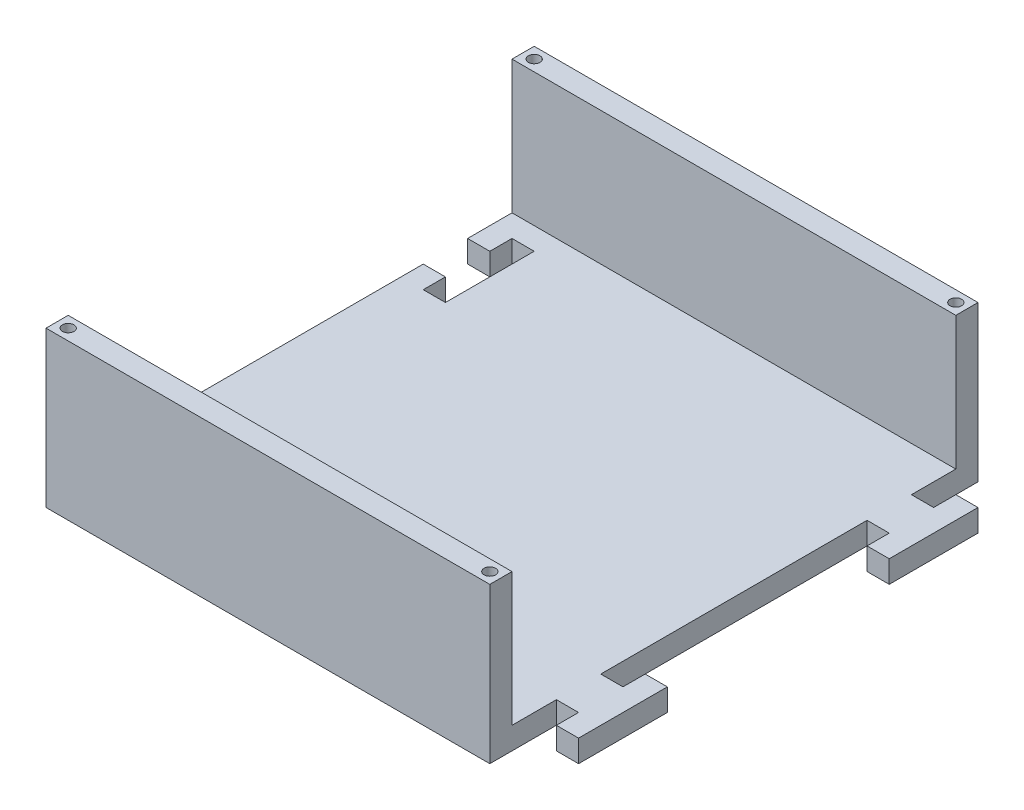
SolidWorks part; units mm, degrees
ref_plane "Front Plane" through (0, 0, 0) normal (0, 0, 1) x (1, 0, 0)
ref_plane "Top Plane" through (0, 0, 0) normal (0, 1, 0) x (1, 0, 0)
ref_plane "Right Plane" through (0, 0, 0) normal (1, 0, 0) x (0, 0, -1)
sketch "Sketch1" plane through (0, 0, 0) normal (0, 1, 0) x (1, 0, 0)
  line L1 (-69.85, -69.85) -> (57.15, -69.85)
  line L2 (-69.85, -69.85) -> (-69.85, 69.85)
  line L3 (-69.85, 69.85) -> (57.15, 69.85)
  line L4 (57.15, -69.85) -> (57.15, 69.85)
  line L5 (-69.85, -69.85) -> (57.15, 69.85) construction
  line L6 (-69.85, 69.85) -> (57.15, -69.85) construction
  point P0 (-6.35, 0)
  dimension "D1" = 127
  dimension "D2" = 139.7
  dimension "D3" = 6.35
extrude "Boss-Extrude1" add sketch "Sketch1" along normal blind 6.35
sketch "Sketch3" plane through (0, 6.35, 0) normal (0, 1, 0) x (1, 0, 0)
  line L0 (57.15, -69.85) -> (57.15, 69.85) construction
  line L1 (-69.85, 69.85) -> (57.15, 69.85)
  line L2 (-69.85, 69.85) -> (-69.85, 63.5)
  line L3 (-69.85, 63.5) -> (57.15, 63.5)
  line L4 (57.15, 69.85) -> (57.15, 63.5)
  line L6 (-69.85, -69.85) -> (57.15, -69.85)
  line L7 (-69.85, -69.85) -> (-69.85, -63.5)
  line L8 (-69.85, -63.5) -> (57.15, -63.5)
  line L9 (57.15, -69.85) -> (57.15, -63.5)
  dimension "D1" = 6.35
extrude "Boss-Extrude2" add sketch "Sketch3" along normal blind 38.1
sketch "Sketch6" plane through (0, 6.35, 0) normal (0, 1, 0) x (1, 0, 0)
  line L0 (57.15, -63.5) -> (57.15, 63.5) construction
  line L1 (57.15, 50.8) -> (63.5, 50.8)
  line L2 (57.15, 50.8) -> (57.15, 38.1)
  line L3 (57.15, 38.1) -> (63.5, 38.1)
  line L5 (57.15, 69.85) -> (-69.85, 69.85) construction
  line L6 (63.5, 57.15) -> (69.85, 57.15)
  line L7 (63.5, 57.15) -> (63.5, 50.8)
  line L8 (63.5, 31.75) -> (69.85, 31.75)
  line L9 (69.85, 57.15) -> (69.85, 31.75)
  line L10 (63.5, 38.1) -> (63.5, 31.75)
  point P10 (69.85, 44.45)
  point P11 (57.15, 44.45)
  dimension "D1" = 6.35
  dimension "D2" = 12.7
  dimension "D3" = 25.4
  dimension "D4" = 6.35
  dimension "D5" = 25.4
extrude "Boss-Extrude3" add sketch "Sketch6" against normal up to surface (6.35 mm away) up to face at (-6.35, 0, 0)
sketch "Sketch7" plane through (0, 6.35, 0) normal (0, 1, 0) x (1, 0, 0)
  line L0 (-69.85, 63.5) -> (-69.85, -63.5) construction
  line L1 (-69.85, 50.8) -> (-63.5, 50.8)
  line L2 (-69.85, 50.8) -> (-69.85, 38.1)
  line L3 (-69.85, 38.1) -> (-63.5, 38.1)
  line L5 (-63.5, 38.1) -> (-63.5, 31.75)
  line L6 (-57.15, 57.15) -> (-63.5, 57.15)
  line L7 (-57.15, 57.15) -> (-57.15, 31.75)
  line L8 (-57.15, 31.75) -> (-63.5, 31.75)
  line L9 (-63.5, 57.15) -> (-63.5, 50.8)
  line L10 (63.5, 50.8) -> (57.15, 50.8) construction
  line L11 (69.85, 57.15) -> (63.5, 57.15) construction
  line L12 (63.5, 57.15) -> (63.5, 50.8) construction
  line L13 (69.85, 31.75) -> (69.85, 57.15) construction
extrude "Cut-Extrude2" cut sketch "Sketch7" against normal through all
mirror "Mirror1" about plane through (0, 0, 0) normal (0, 0, 1) of "Boss-Extrude3", "Cut-Extrude2"
sketch "Sketch8" plane through (0, 44.45, 0) normal (0, 1, 0) x (1, 0, 0)
  line L0 (-69.85, 69.85) -> (-63.5, 63.5) construction
  line L1 (-69.85, 63.5) -> (57.15, 63.5) construction
  line L2 (-69.85, 69.85) -> (-69.85, 63.5) construction
  circle A0 centre (-66.675, 66.675) radius 1.65
  dimension "D2" = 3.3
  dimension "D1" = 45
extrude "Cut-Extrude3" cut sketch "Sketch8" against normal blind 12
ref_plane "Plane1" through (-6.35, 0, 0) normal (-1, 0, 0) x (0, 0, 1)
mirror "Mirror2" about plane through (0, 0, 0) normal (0, 0, 1) of "Cut-Extrude3" second plane through (-6.35, 0, 0) second plane normal (-1, 0, 0)
